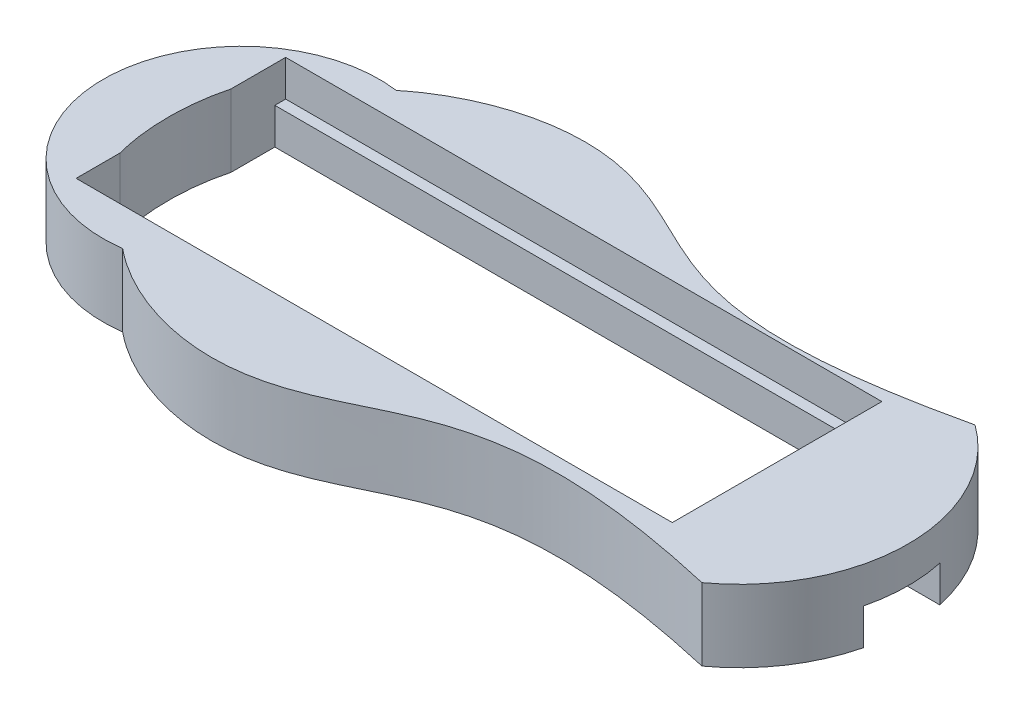
SolidWorks part; units mm, degrees
ref_plane "Front Plane" through (0, 0, 0) normal (0, 0, 1) x (1, 0, 0)
ref_plane "Top Plane" through (0, 0, 0) normal (0, 1, 0) x (1, 0, 0)
ref_plane "Right Plane" through (0, 0, 0) normal (1, 0, 0) x (0, 0, -1)
sketch "Sketch1" plane through (0, 0, 0) normal (0, 1, 0) x (1, 0, 0)
  line L0 (145.2959, 60.8322) -> (44.1561, 37.6351) construction
  line L1 (44.1561, 37.6351) -> (68.5985, 81.4749) construction
  line L2 (68.5985, 81.4749) -> (14.8614, 85.461) construction
  line L3 (-38.2103, -4.4601) -> (126.7897, -4.4601)
  line L4 (-38.2103, -4.4601) -> (-38.2103, 50.5399)
  line L5 (-38.2103, 50.5399) -> (126.7897, 50.5399)
  line L6 (126.7897, -4.4601) -> (126.7897, 50.5399)
  line L7 (-38.2103, -4.4601) -> (126.7897, 50.5399) construction
  line L8 (-38.2103, 50.5399) -> (126.7897, -4.4601) construction
  line L9 (14.8614, 85.461) -> (-14.9447, 60.9246) construction
  line L10 (-38.2103, 23.0399) -> (126.7897, 23.0399) construction
  line L11 (145.2959, -14.7524) -> (44.1561, 8.4446) construction
  line L12 (44.1561, 8.4446) -> (68.5985, -35.3952) construction
  line L13 (68.5985, -35.3952) -> (14.8614, -39.3813) construction
  line L14 (14.8614, -39.3813) -> (-14.9447, -14.8449) construction
  arc A0 (-14.9447, 60.9246) -> (-14.9447, -14.8449) centre (-19.9936, 23.0399) ccw
  arc A1 (145.2959, -14.7524) -> (145.2959, 60.8322) centre (117.8803, 23.0399) ccw
  ellipse E0 centre (28.7074, 23.0399) end of major axis (-4.5093, 23.0399) minor radius 20.9366
  ellipse E1 centre (-24.8419, 23.0399) end of major axis (-24.8419, -8.5218) minor radius 15.2998
  spline S0 degree 4 poles (145.2959, 60.8322) (44.1561, 37.6351) (68.5985, 81.4749) (14.8614, 85.461) (-14.9447, 60.9246) knots 0 0 0 0 0 1 1 1 1 1
  spline S1 degree 4 poles (145.2959, -14.7524) (44.1561, 8.4446) (68.5985, -35.3952) (14.8614, -39.3813) (-14.9447, -14.8449) knots 0 0 0 0 0 1 1 1 1 1
  point P9 (44.2897, 23.0399)
  dimension "D3" = 167.3962
  dimension "D4" = 165
  dimension "D1" = 165
  dimension "D2" = 55
extrude "Boss-Extrude1" add sketch "Sketch1" along normal blind 20 contours S1 A1 S0 A0 E1 L5 L6 L3 L4 | L5 E1 | L3 E1
sketch "Sketch4" plane through (0, 20, 0) normal (0, 1, 0) x (1, 0, 0)
  line L1 (-38.2103, 50.5399) -> (126.7897, 50.5399)
  line L2 (-38.2103, 50.5399) -> (-38.2103, 53.5399)
  line L3 (-38.2103, 53.5399) -> (126.7897, 53.5399)
  line L4 (126.7897, 50.5399) -> (126.7897, 53.5399)
  line L5 (-38.2103, 50.5399) -> (126.7897, 53.5399) construction
  line L6 (-38.2103, 53.5399) -> (126.7897, 50.5399) construction
  point P4 (44.2897, 52.0399)
  dimension "D1" = 165
  dimension "D2" = 3
extrude "Cut-Extrude1" cut sketch "Sketch4" against normal blind 10
sketch "Sketch9" plane through (0, 0, 0) normal (0, -1, 0) x (1, 0, 0)
  line L0 (126.7897, 4.4601) -> (126.7897, -50.5399) construction
  line L1 (126.7897, -11.9953) -> (168.2058, -11.9953)
  line L2 (126.7897, -11.9953) -> (126.7897, -32.8123)
  line L3 (126.7897, -32.8123) -> (168.2058, -32.8123)
  line L4 (168.2058, -11.9953) -> (168.2058, -32.8123)
  line L5 (126.7897, -11.9953) -> (168.2058, -32.8123) construction
  line L6 (126.7897, -32.8123) -> (168.2058, -11.9953) construction
  point P4 (147.4978, -22.4038)
extrude "Cut-Extrude2" cut sketch "Sketch9" against normal blind 10
